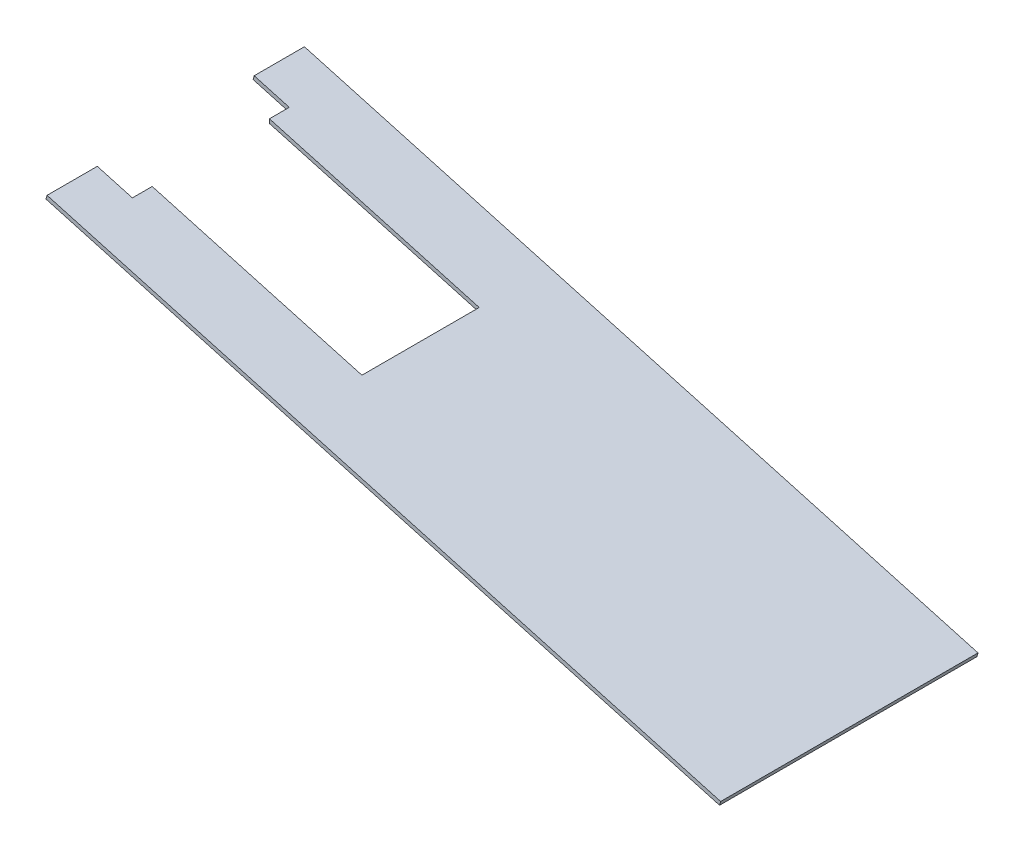
SolidWorks part; units mm, degrees
ref_plane "Plan de face" through (0, 0, 0) normal (0, 0, 1) x (1, 0, 0)
ref_plane "Plan de dessus" through (0, 0, 0) normal (0, 1, 0) x (1, 0, 0)
ref_plane "Plan de droite" through (0, 0, 0) normal (1, 0, 0) x (0, 0, -1)
sketch "Esquisse1" plane through (0, 0, 0) normal (0, 0, 1) x (1, 0, 0)
  line L0 (-99.3467, 52.868) -> (258.5213, -47.0952)
  line L1 (258.5213, -47.0952) -> (259.0594, -45.1689)
  line L2 (259.0594, -45.1689) -> (-98.8086, 54.7942)
  line L3 (-260.4787, 52.9048) -> (-99.6157, 52.9048)
  line L4 (-99.6157, 54.9048) -> (-260.4787, 54.9048)
  line L5 (-263.4787, -47.0952) -> (-261.4787, -47.0952)
  line L6 (-261.4787, -47.0952) -> (-261.4787, 51.9048)
  line L7 (-263.4787, 51.9048) -> (-263.4787, -47.0952)
  arc A0 (-99.3467, 52.868) -> (-99.6157, 52.9048) centre (-99.6157, 51.9048) ccw
  arc A1 (-98.8086, 54.7942) -> (-99.6157, 54.9048) centre (-99.6157, 51.9048) ccw
  arc A2 (-260.4787, 52.9048) -> (-261.4787, 51.9048) centre (-260.4787, 51.9048) ccw
  arc A3 (-260.4787, 54.9048) -> (-263.4787, 51.9048) centre (-260.4787, 51.9048) ccw
extrude "Boss.-Extru.1" add sketch "Esquisse1" along normal blind 130
sketch "Esquisse2" plane through (0, -47.0952, 0) normal (0, -1, 0) x (1, 0, 0)
  line L4 (-263.4787, 0) -> (-261.4787, 0)
  line L5 (-261.4787, 0) -> (-261.4787, 130)
  line L6 (-261.4787, 130) -> (-263.4787, 130)
  line L7 (-263.4787, 130) -> (-263.4787, 0)
  line L8 (-263.4787, 0) -> (-261.4787, 0)
  line L9 (-261.4787, 0) -> (-261.4787, 130)
  line L10 (-261.4787, 130) -> (-263.4787, 130)
  line L11 (-263.4787, 130) -> (-263.4787, 0)
  dimension "D1" = 0
extrude "Boss.-Extru.2" add sketch "Esquisse2" along normal blind 96
sketch "Esquisse3" plane through (-263.4787, 0, 0) normal (-1, 0, 0) x (0, 0, 1)
  line L0 (130, -143.0952) -> (0, -143.0952) construction
  line L1 (104.6215, 57.5782) -> (25.3785, 57.5782)
  line L2 (104.6215, 57.5782) -> (104.6215, -93.0952)
  line L3 (104.6215, -93.0952) -> (25.3785, -93.0952)
  line L4 (25.3785, 57.5782) -> (25.3785, -93.0952)
  line L5 (104.6215, 57.5782) -> (25.3785, -93.0952) construction
  line L6 (104.6215, -93.0952) -> (25.3785, 57.5782) construction
  point P0 (65, -17.7585)
  dimension "D1" = 50
extrude "Enlèv. mat.-Extru.1" cut sketch "Esquisse3" against normal blind 200
sketch "Sketch1" plane through (7.0463, 25.2258, 0) normal (0.269, 0.9631, 0) x (0.9631, -0.269, 0)
  line L1 (-615.502, 464.9681) -> (-111.2052, 464.9681)
  line L2 (-615.502, 464.9681) -> (-615.502, -169.3963)
  line L3 (-615.502, -169.3963) -> (-111.2052, -169.3963)
  line L4 (-111.2052, 464.9681) -> (-111.2052, -169.3963)
  line L5 (-615.502, 464.9681) -> (-111.2052, -169.3963) construction
  line L6 (-615.502, -169.3963) -> (-111.2052, 464.9681) construction
  point P0 (-363.3536, 147.7859)
extrude "Cut-Extrude1" cut sketch "Sketch1" against normal through all
sketch "Sketch2" plane through (7.0463, 25.2258, 0) normal (0.269, 0.9631, 0) x (0.9631, -0.269, 0)
  line L1 (-165.6714, 39.8921) -> (-91.6299, 39.8921)
  line L2 (-165.6714, 39.8921) -> (-165.6714, -146.5338)
  line L3 (-165.6714, -146.5338) -> (-91.6299, -146.5338)
  line L4 (-91.6299, 39.8921) -> (-91.6299, -146.5338)
extrude "Cut-Extrude3" cut sketch "Sketch2" against normal through all
sketch "Sketch3" plane through (7.0463, 25.2258, 0) normal (0.269, 0.9631, 0) x (0.9631, -0.269, 0)
  line L0 (-73.2247, -25.3785) -> (-73.2247, -104.6215) construction
  line L1 (-73.2247, -35.3785) -> (36.7753, -35.3785)
  line L2 (-73.2247, -35.3785) -> (-73.2247, -94.6215)
  line L3 (-73.2247, -94.6215) -> (36.7753, -94.6215)
  line L4 (36.7753, -35.3785) -> (36.7753, -94.6215)
  line L5 (-91.6299, -25.3785) -> (-73.2247, -25.3785) construction
  line L6 (-73.2247, -104.6215) -> (-91.6299, -104.6215) construction
  dimension "D1" = 10
  dimension "D2" = 10
  dimension "D3" = 110
extrude "Cut-Extrude4" cut sketch "Sketch3" against normal through all
